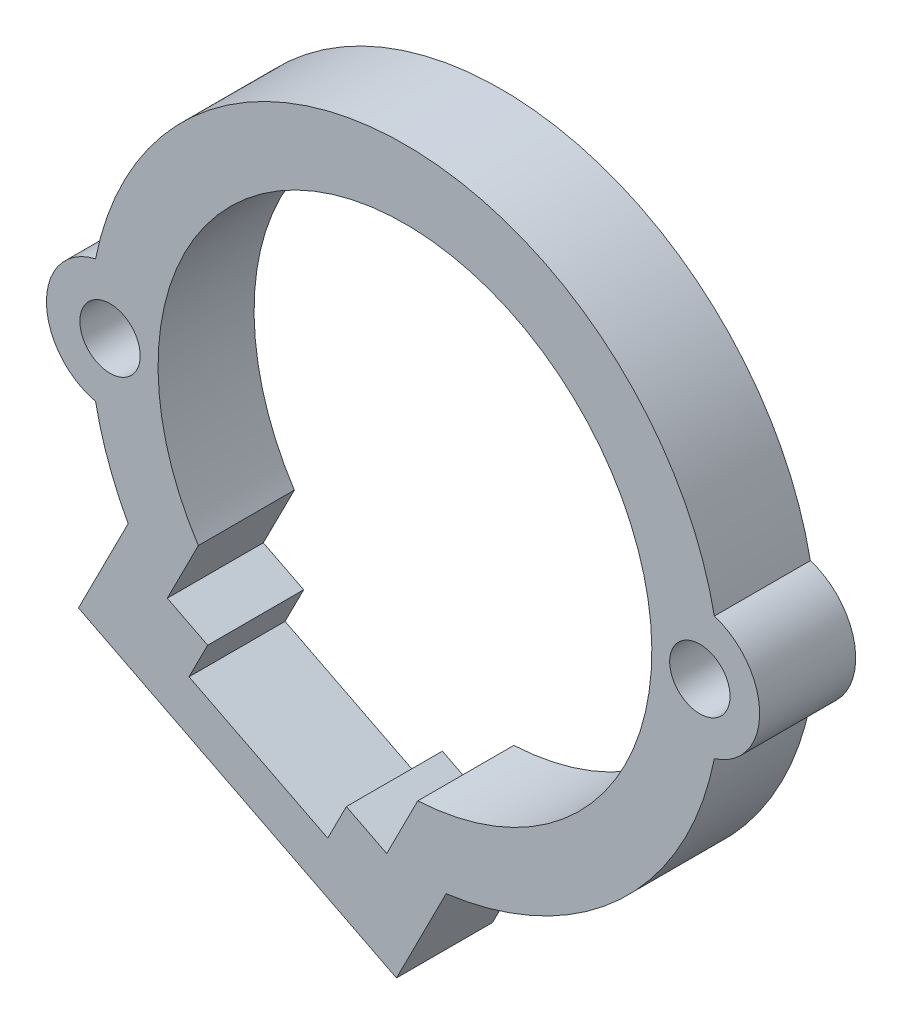
SolidWorks part; units mm, degrees
ref_plane "Front Plane" through (0, 0, 0) normal (0, 0, 1) x (1, 0, 0)
ref_plane "Top Plane" through (0, 0, 0) normal (0, 1, 0) x (1, 0, 0)
ref_plane "Right Plane" through (0, 0, 0) normal (1, 0, 0) x (0, 0, -1)
sketch "Sketch1" plane through (0, 0, 0) normal (0, 0, 1) x (1, 0, 0)
  circle A0 centre (0, 0) radius 23
  circle A1 centre (0, 0) radius 18
  dimension "D1" = 36
  dimension "D2" = 5
extrude "Boss-Extrude1" add sketch "Sketch1" along normal blind 7
sketch "Sketch3" plane through (0, 0, 0) normal (0, 0, 1) x (1, 0, 0)
  line L0 (-23.8014, -18.1679) -> (-0.6174, -29.9366)
  line L1 (-0.6174, -29.9366) -> (3.0037, -22.803)
  line L2 (-23.8014, -18.1679) -> (-20.1803, -11.0343)
  circle A0 centre (0, 0) radius 23 construction
  arc A2 (-20.1803, -11.0343) -> (3.0037, -22.803) centre (0, 0) ccw
  dimension "D1" = 26
  dimension "D2" = 8
  dimension "D3" = 8
extrude "Boss-Extrude2" add sketch "Sketch3" along normal blind 7
sketch "Sketch5" plane through (0, 0, 0) normal (0, 0, 1) x (1, 0, 0)
  line L0 (-15.0623, -9.8553) -> (-17.3255, -14.3138)
  line L1 (-17.3255, -14.3138) -> (-1.3285, -22.4342)
  line L2 (-1.3285, -22.4342) -> (0.9347, -17.9757)
  line L4 (-23.8014, -18.1679) -> (-0.6174, -29.9366) construction
  circle A0 centre (0, 0) radius 18 construction
  arc A1 (0.9347, -17.9757) -> (-15.0623, -9.8553) centre (0, 0) cw
  dimension "D1" = 17.94
  dimension "D2" = 5
  dimension "D3" = 5
extrude "Cut-Extrude1" cut sketch "Sketch5" along normal blind 7
sketch "Sketch6" plane through (0, 0, 0) normal (0, 0, 1) x (1, 0, 0)
  arc A0 (-22.5555, -4.5) -> (-22.5555, 4.5) centre (-21.5191, 0) cw
  circle A1 centre (0, 0) radius 23 construction
  arc A2 (22.5555, -4.5) -> (22.5555, 4.5) centre (21.1441, 0) ccw
  arc A3 (-22.5555, -4.5) -> (-22.5555, 4.5) centre (0, 0) cw
  arc A4 (22.5555, -4.5) -> (22.5555, 4.5) centre (0, 0) ccw
  dimension "D1" = 4.5
  dimension "D2" = 4.5
  dimension "D3" = 4.5
  dimension "D4" = 4.5
extrude "Boss-Extrude3" add sketch "Sketch6" along normal blind 7
sketch "Sketch7" plane through (0, 0, 0) normal (0, 0, 1) x (1, 0, 0)
  circle A0 centre (-21.5, 0) radius 2.2
  circle A1 centre (21.5, 0) radius 2.2
  dimension "D1" = 4.4
  dimension "D2" = 21.5
  dimension "D3" = 21.5
extrude "Cut-Extrude2" cut sketch "Sketch7" along normal blind 7
sketch "Sketch8" plane through (0, 0, 0) normal (0, 0, 1) x (1, 0, 0)
  line L0 (-14.3829, -15.8075) -> (-4.2711, -20.9405)
  line L1 (-17.3255, -14.3138) -> (-1.3285, -22.4342) construction
  line L2 (-4.2711, -20.9405) -> (-5.629, -23.6155)
  line L3 (-5.629, -23.6155) -> (-15.7408, -18.4826)
  line L4 (-15.7408, -18.4826) -> (-14.3829, -15.8075)
  line L5 (-15.0623, -9.8553) -> (-17.3255, -14.3138) construction
  line L6 (-1.3285, -22.4342) -> (0.9347, -17.9757) construction
  dimension "D1" = 3
  dimension "D2" = 3
  dimension "D3" = 3.3
  dimension "D4" = 3.3
extrude "Cut-Extrude3" cut sketch "Sketch8" along normal blind 7
